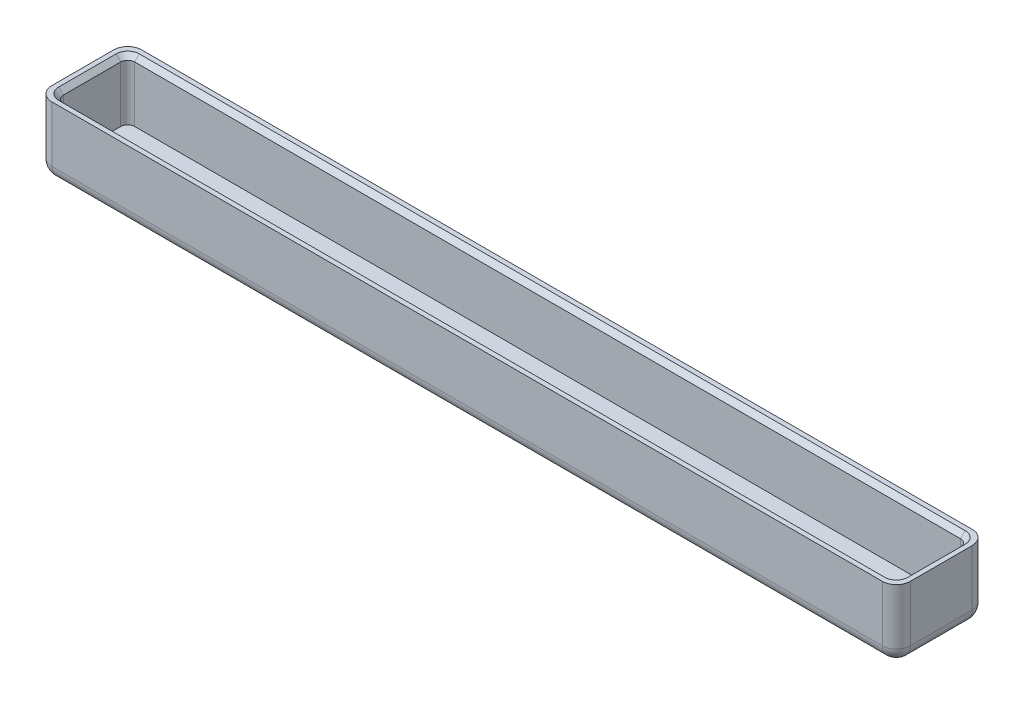
SolidWorks part; units mm, degrees
ref_plane "Front Plane" through (0, 0, 0) normal (0, 0, 1) x (1, 0, 0)
ref_plane "Top Plane" through (0, 0, 0) normal (0, 1, 0) x (1, 0, 0)
ref_plane "Right Plane" through (0, 0, 0) normal (1, 0, 0) x (0, 0, -1)
sketch "Sketch2" plane through (0, 0, 0) normal (0, 1, 0) x (1, 0, 0)
  line L1 (-92.15, -9.65) -> (92.15, -9.65)
  line L2 (-92.15, -9.65) -> (-92.15, 9.65)
  line L3 (-92.15, 9.65) -> (92.15, 9.65)
  line L4 (92.15, -9.65) -> (92.15, 9.65)
  line L5 (-92.15, -9.65) -> (92.15, 9.65) construction
  line L6 (-92.15, 9.65) -> (92.15, -9.65) construction
  point P0 (0, 0)
  dimension "D1" = 19.3
  dimension "D2" = 184.3
extrude "Boss-Extrude1" add sketch "Sketch2" along normal blind 15
shell "Shell1" thickness 2
fillet "Fillet1" radius 3 8 edges at (0, 0, -9.65) (-92.15, 0, 0) (0, 0, 9.65) (92.15, 0, 0) (92.15, 7.5, 9.65) (92.15, 7.5, -9.65) (-92.15, 7.5, -9.65) (-92.15, 7.5, 9.65)
fillet "Fillet2" radius 1.5 4 edges at (90.15, 8.5, 7.65) (90.15, 8.5, -7.65) (-90.15, 8.5, 7.65) (-90.15, 8.5, -7.65)
chamfer "Chamfer1" distance 1 angle 45 8 edges at (90.15, 15, 0) (89.7107, 15, -7.2107) (89.7107, 15, 7.2107) (0, 15, -7.65) (0, 15, 7.65) (-89.7107, 15, -7.2107) (-89.7107, 15, 7.2107) (-90.15, 15, 0)
